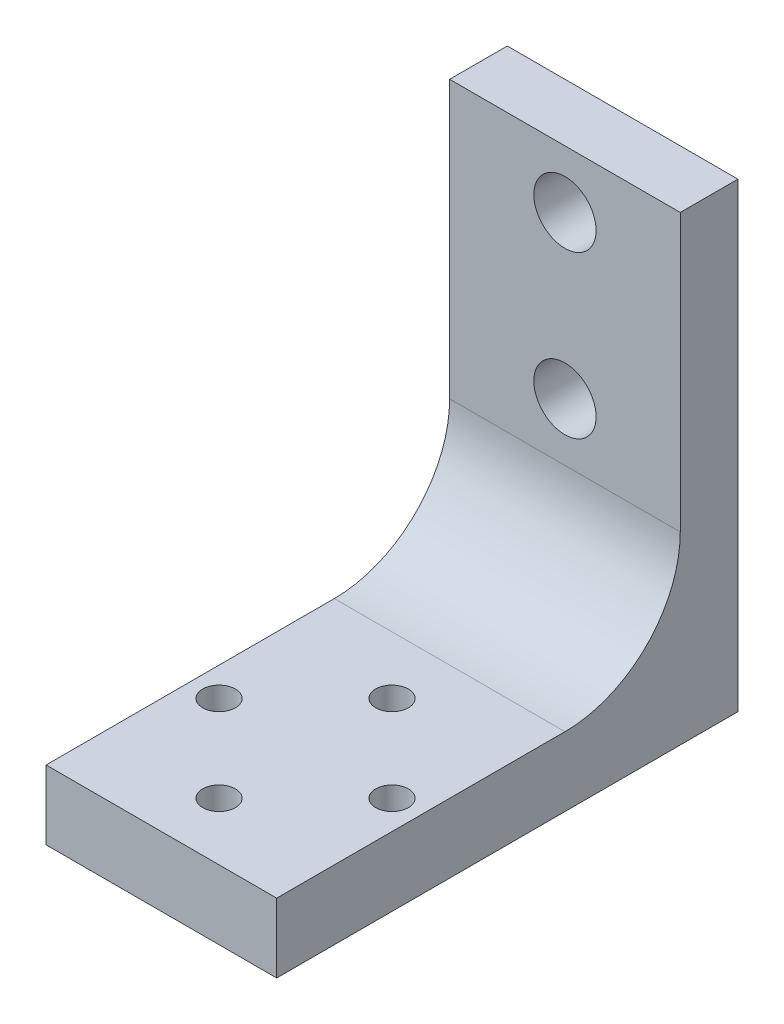
SolidWorks part; units mm, degrees
ref_plane "Front Plane" through (0, 0, 0) normal (0, 0, 1) x (1, 0, 0)
ref_plane "Top Plane" through (0, 0, 0) normal (0, 1, 0) x (1, 0, 0)
ref_plane "Right Plane" through (0, 0, 0) normal (1, 0, 0) x (0, 0, -1)
sketch "Sketch1" plane through (0, 0, 0) normal (0, 0, 1) x (1, 0, 0)
  line L1 (0, 0) -> (25.4, 0)
  line L2 (0, 0) -> (0, 50.8)
  line L3 (0, 50.8) -> (25.4, 50.8)
  line L4 (25.4, 0) -> (25.4, 50.8)
  dimension "D1" = 25.4
  dimension "D2" = 50.8
extrude "Boss-Extrude1" add sketch "Sketch1" along normal blind 6.35
sketch "Sketch2" plane through (25.4, 0, 0) normal (1, 0, 0) x (0, 0, -1)
  line L0 (-6.35, 0) -> (-50.8, 0)
  line L2 (-50.8, 0) -> (-50.8, 7.62)
  line L3 (-50.8, 7.62) -> (-6.35, 7.62)
  line L4 (-6.35, 0) -> (-6.35, 50.8) construction
  line L5 (-6.35, 7.62) -> (-6.35, 0)
  dimension "D1" = 7.62
  dimension "D2" = 44.45
extrude "Boss-Extrude2" add sketch "Sketch2" against normal blind 25.4
fillet "Fillet1" radius 12.7 1 edges at (12.7, 7.62, 6.35)
sketch "Sketch3" plane through (0, 0, 6.35) normal (0, 0, 1) x (1, 0, 0)
  line L0 (12.7, 50.8) -> (12.7, 20.32) construction
  line L1 (25.4, 50.8) -> (0, 50.8) construction
  line L2 (0, 20.32) -> (25.4, 20.32) construction
  circle A0 centre (12.7, 44.45) radius 3.429
  circle A1 centre (12.7, 26.67) radius 3.429
  dimension "D1" = 6.858
  dimension "D2" = 6.35
  dimension "D3" = 6.35
extrude "Cut-Extrude1" cut sketch "Sketch3" against normal up to surface (6.35 mm away) up to face at (12.7, 25.4, 0)
sketch "Sketch4" plane through (0, 7.62, 0) normal (0, 1, 0) x (1, 0, 0)
  line L2 (12.7, -25.4) -> (3.175, -34.925) construction
  line L3 (3.175, -34.925) -> (12.7, -44.45) construction
  line L4 (12.7, -44.45) -> (22.225, -34.925) construction
  line L5 (22.225, -34.925) -> (12.7, -25.4) construction
  line L6 (12.7, -19.05) -> (12.7, -64.1745) construction
  line L7 (25.4, -19.05) -> (0, -19.05) construction
  circle A0 centre (12.7, -25.4) radius 1.8
  circle A1 centre (22.225, -34.925) radius 1.8
  circle A2 centre (12.7, -44.45) radius 1.8
  circle A3 centre (3.175, -34.925) radius 1.8
  dimension "D4" = 3.6
  dimension "D1" = 19.05
  dimension "D2" = 19.05
  dimension "D3" = 6.35
extrude "Cut-Extrude2" cut sketch "Sketch4" against normal up to surface (7.62 mm away) up to face at (12.7, 0, 25.4)
